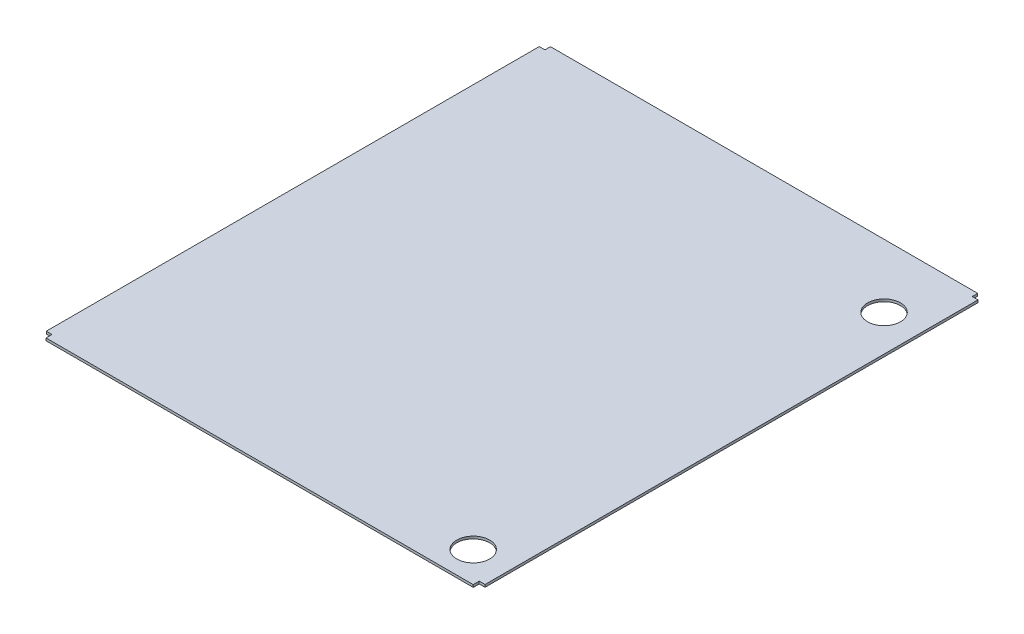
SolidWorks part; units mm, degrees
ref_plane "Front Plane" through (0, 0, 0) normal (0, 0, 1) x (1, 0, 0)
ref_plane "Top Plane" through (0, 0, 0) normal (0, 1, 0) x (1, 0, 0)
ref_plane "Right Plane" through (0, 0, 0) normal (1, 0, 0) x (0, 0, -1)
sketch "Sketch1" plane through (0, 0, 0) normal (0, 1, 0) x (1, 0, 0)
  line L1 (0.0465, 0.2911) -> (534.0465, 0.2911)
  line L2 (0.0465, 0.2911) -> (0.0465, 600.2911)
  line L3 (0.0465, 600.2911) -> (534.0465, 600.2911)
  line L4 (534.0465, 0.2911) -> (534.0465, 600.2911)
extrude "Boss-Extrude1" add sketch "Sketch1" along normal blind 3
ref_plane "Plane1" through (534.0465, 3, -600.2911) normal (0, 0, -1) x (-1, 0, 0)
sketch "Sketch3" plane through (0, 0, 0) normal (0, 1, 0) x (1, 0, 0)
  line L1 (7, 607) -> (527, 607)
  line L2 (7, 607) -> (7, -7)
  line L3 (7, -7) -> (527, -7)
  line L4 (527, 607) -> (527, -7)
extrude "Boss-Extrude2" add sketch "Sketch3" along normal blind 3
sketch "Sketch4" plane through (0, 3, 0) normal (0, 1, 0) x (1, 0, 0)
  circle A0 centre (490, 530) radius 20
sketch "Sketch5" plane through (0, 0, 0) normal (0, -1, 0) x (-1, 0, 0)
  circle A0 centre (-490, 30) radius 20
extrude "Cut-Extrude5" cut sketch "Sketch4" against normal blind 10
extrude "Cut-Extrude7" cut sketch "Sketch5" against normal blind 10 contours A0
